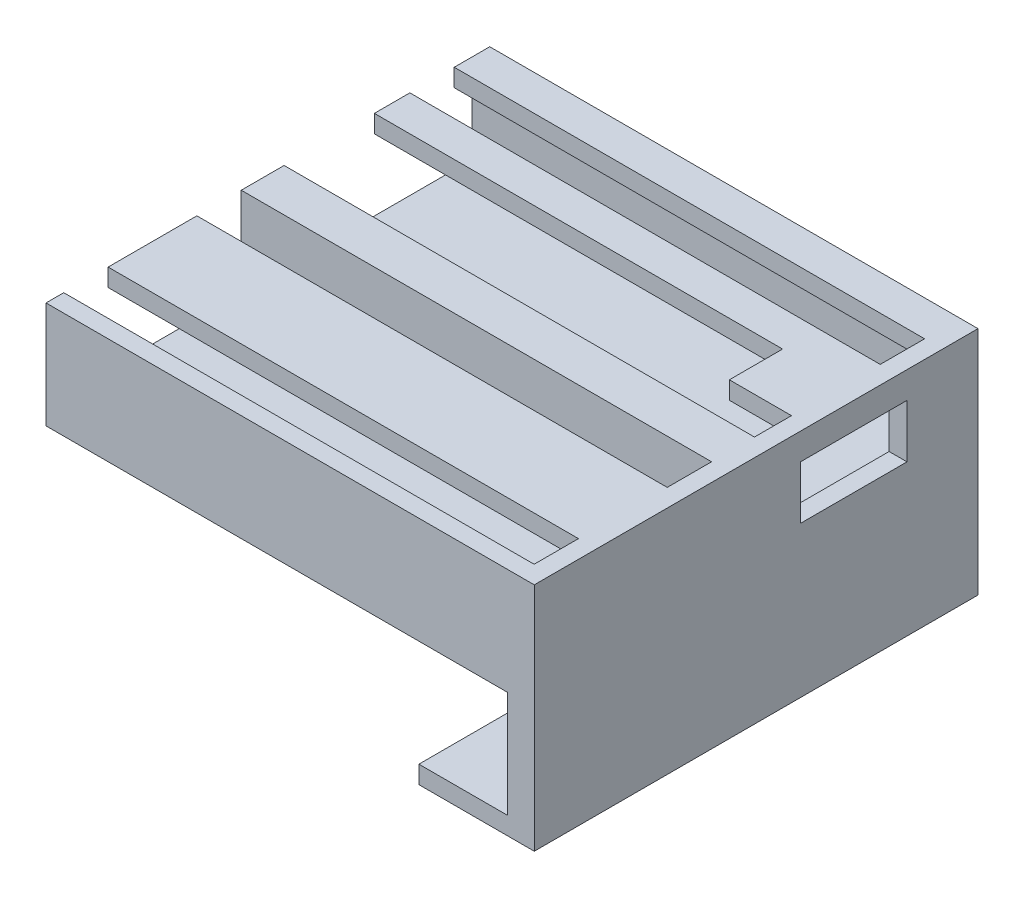
SolidWorks part; units mm, degrees
ref_plane "前视基准面" through (0, 0, 0) normal (0, 0, 1) x (1, 0, 0)
ref_plane "上视基准面" through (0, 0, 0) normal (0, 1, 0) x (1, 0, 0)
ref_plane "右视基准面" through (0, 0, 0) normal (1, 0, 0) x (0, 0, -1)
sketch "草图1" plane through (0, 0, 0) normal (0, 1, 0) x (1, 0, 0)
  line L0 (-42.6056, 28.8972) -> (12.3944, 28.8972)
  line L1 (12.3944, 28.8972) -> (12.3944, -21.1028)
  line L2 (12.3944, -21.1028) -> (-42.6056, -21.1028)
  line L3 (-42.6056, -21.1028) -> (-42.6056, 28.8972)
  dimension "D1" = 50
  dimension "D2" = 55
extrude "凸台-拉伸1" add sketch "草图1" along normal blind 2
sketch "草图2" plane through (0, 2, 0) normal (0, 1, 0) x (1, 0, 0)
  line L0 (12.3944, -21.1028) -> (12.3944, 28.8972) construction
  line L1 (10.3779, 28.8972) -> (12.3944, 28.8972)
  line L2 (12.3944, 28.8972) -> (12.3944, -21.1028)
  line L3 (12.3944, -21.1028) -> (10.3779, -21.1028)
  line L4 (10.3779, -21.1028) -> (10.3779, 28.8972)
  dimension "D1" = 55
  dimension "D2" = 2.0164
  dimension "D3" = 50
extrude "凸台-拉伸2" add sketch "草图2" along normal blind 10
sketch "草图4" plane through (10.3779, 0, 0) normal (-1, 0, 0) x (0, 0, 1)
  line L0 (-19.8972, 12) -> (-19.8972, 10)
  line L2 (-19.8972, 10) -> (-9.8972, 10)
  line L3 (-9.8972, 10) -> (-9.8972, 12)
  line L4 (-9.8972, 12) -> (-19.8972, 12)
  line L6 (-28.8972, 12) -> (-26.8972, 12)
  line L7 (-26.8972, 10) -> (-26.8972, 2)
  line L8 (-28.8972, 2) -> (21.1028, 2) construction
  line L9 (-26.8972, 2) -> (-28.8972, 2)
  line L10 (-28.8972, 2) -> (-28.8972, 12)
  line L11 (-2.8972, 10) -> (-2.8972, 2)
  line L12 (-28.8972, 2) -> (21.1028, 2) construction
  line L13 (-2.8972, 2) -> (-0.8972, 2)
  line L14 (-0.8972, 2) -> (-0.8972, 12)
  line L15 (-0.8972, 12) -> (-2.8972, 12)
  line L16 (4.1028, 12) -> (4.1028, 10)
  line L18 (4.1028, 10) -> (14.1028, 10)
  line L19 (14.1028, 10) -> (14.1028, 12)
  line L20 (14.1028, 12) -> (4.1028, 12)
  line L21 (19.1028, 12) -> (21.1028, 12)
  line L22 (21.1028, 12) -> (21.1028, 2)
  line L23 (-28.8972, 2) -> (21.1028, 2) construction
  line L24 (21.1028, 2) -> (19.1028, 2)
  line L25 (19.1028, 2) -> (19.1028, 12)
  line L26 (-26.8972, 12) -> (-24.8972, 12)
  line L27 (-24.8972, 12) -> (-24.8972, 10)
  line L28 (-24.8972, 10) -> (-26.8972, 10)
  line L29 (-2.8972, 10) -> (-5.7256, 10)
  line L30 (-5.7256, 10) -> (-5.7256, 12)
  line L31 (-5.7256, 12) -> (-2.8972, 12)
  point P4 (-14.8972, 12)
  dimension "D2" = 2
  dimension "D4" = 12
  dimension "D5" = 5
  dimension "D6" = 10
  dimension "D7" = 2
  dimension "D8" = 5
  dimension "D9" = 24
  dimension "D10" = 20
  dimension "D11" = 8
  dimension "D12" = 8
  dimension "D13" = 2
extrude "凸台-拉伸3" add sketch "草图4" along normal blind 53
sketch "草图5" plane through (12.3944, 0, 0) normal (1, 0, 0) x (0, 0, -1)
  line L0 (8.8972, 9) -> (8.8972, 3)
  line L1 (8.8972, 3) -> (20.8972, 3)
  line L2 (20.8972, 3) -> (20.8972, 9)
  line L3 (20.8972, 9) -> (8.8972, 9)
  line L5 (28.8972, 2) -> (-21.1028, 2) construction
  line L7 (28.8972, 12) -> (28.8972, 0) construction
  line L9 (-21.1028, 0) -> (28.8972, 0) construction
  dimension "D1" = 12
  dimension "D2" = 8
  dimension "D3" = 6
  dimension "D5" = 3
extrude "切除-拉伸1" cut sketch "草图5" against normal blind 40
sketch "草图6" plane through (0, 12, 0) normal (0, 1, 0) x (1, 0, 0)
  line L0 (3.3779, 9.8972) -> (3.3779, 15.8972)
  line L1 (-42.6221, 9.8972) -> (10.3779, 9.8972) construction
  line L2 (3.3779, 15.8972) -> (-42.6221, 15.8972)
  line L3 (-42.6221, 15.8972) -> (-42.6221, 9.8972)
  line L4 (-42.6221, 9.8972) -> (3.3779, 9.8972)
  line L5 (-42.6221, 19.8972) -> (10.3779, 19.8972) construction
  line L7 (-42.6221, 9.8972) -> (-42.6221, 19.8972) construction
  dimension "D1" = 7
  dimension "D2" = 4
extrude "切除-拉伸3" cut sketch "草图6" against normal blind 2 contours L3 L4 L0 L2
sketch "草图7" plane through (0, 0, 0) normal (0, -1, 0) x (1, 0, 0)
  line L0 (12.3944, 21.1028) -> (9.3944, 21.1028)
  line L1 (-42.6056, 21.1028) -> (12.3944, 21.1028) construction
  line L2 (9.3944, 21.1028) -> (9.3944, -28.8972)
  line L3 (12.3944, -28.8972) -> (-42.6056, -28.8972) construction
  line L4 (9.3944, -28.8972) -> (12.3944, -28.8972)
  line L5 (12.3944, 21.1028) -> (12.3944, -28.8972) construction
  line L6 (12.3944, -28.8972) -> (12.3944, 21.1028)
extrude "凸台-拉伸4" add sketch "草图7" along normal blind 14
sketch "草图8" plane through (9.3944, 0, 0) normal (-1, 0, 0) x (0, 0, 1)
  line L0 (21.1028, -14) -> (-28.8972, -14)
  line L1 (-28.8972, -14) -> (-28.8972, -12)
  line L2 (-28.8972, -14) -> (-28.8972, 0) construction
  line L3 (-28.8972, -12) -> (21.1028, -12)
  line L4 (21.1028, -14) -> (21.1028, 0) construction
  line L5 (21.1028, -12) -> (21.1028, -14)
extrude "凸台-拉伸5" add sketch "草图8" along normal blind 10
